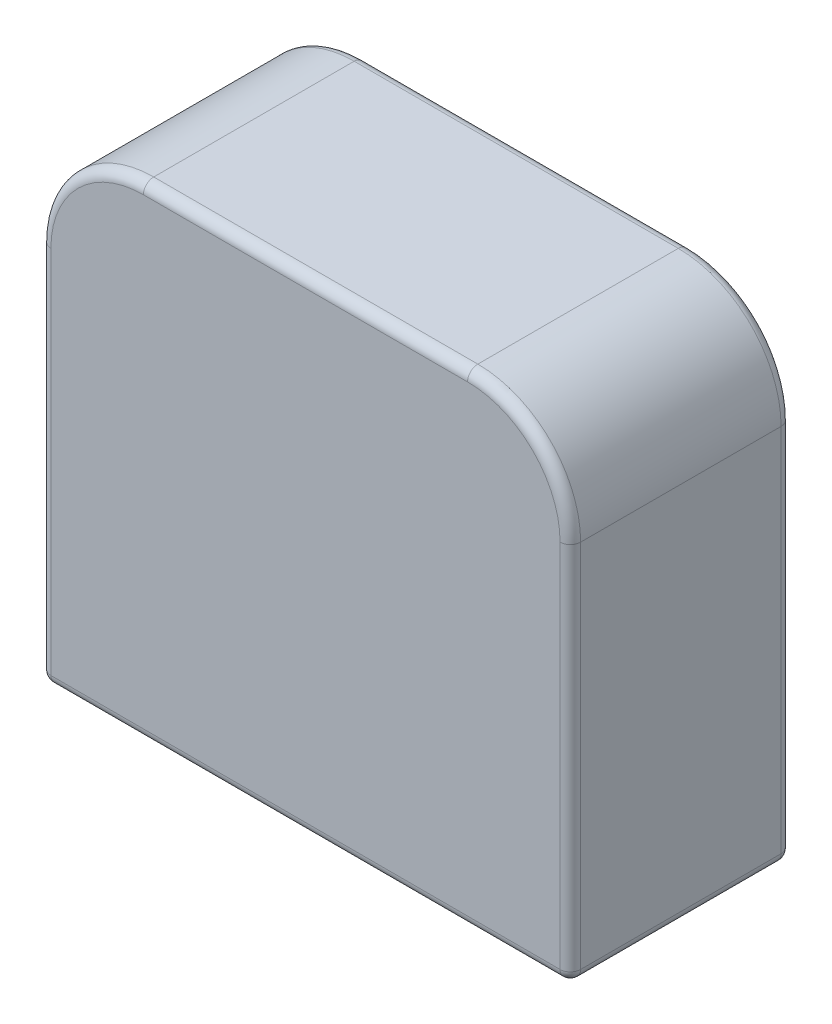
SolidWorks part; units mm, degrees
ref_plane "Alzado" through (0, 0, 0) normal (0, 0, 1) x (1, 0, 0)
ref_plane "Planta" through (0, 0, 0) normal (0, 1, 0) x (1, 0, 0)
ref_plane "Vista lateral" through (0, 0, 0) normal (1, 0, 0) x (0, 0, -1)
sketch "Croquis1" plane through (0, 0, 0) normal (0, 0, 1) x (1, 0, 0)
  line L1 (-25.765, 23.5) -> (25.765, 23.5)
  line L2 (-25.765, 23.5) -> (-25.765, -23.5)
  line L3 (-25.765, -23.5) -> (25.765, -23.5)
  line L4 (25.765, 23.5) -> (25.765, -23.5)
  line L5 (-25.765, 23.5) -> (25.765, -23.5) construction
  line L6 (-25.765, -23.5) -> (25.765, 23.5) construction
  point P0 (0, 0)
  dimension "D1" = 51.53
  dimension "D2" = 47
extrude "Saliente-Extruir1" add sketch "Croquis1" along normal blind 21.5
fillet "Redondeo4" radius 10 2 edges at (-25.765, 23.5, 10.75) (25.765, 23.5, 10.75)
fillet "Redondeo3" radius 1 14 edges at (-25.765, -23.5, 10.75) (0, -23.5, 0) (0, 23.5, 0) (-25.765, -5, 0) (25.765, -5, 0) (25.765, -23.5, 10.75) (0, -23.5, 21.5) (-25.765, -5, 21.5) (25.765, -5, 21.5) (0, 23.5, 21.5) (-22.8361, 20.5711, 0) (22.8361, 20.5711, 0) (-22.8361, 20.5711, 21.5) (22.8361, 20.5711, 21.5)
sketch "Croquis2" plane through (0, 0, 0) normal (0, 0, 1) x (1, 0, 0)
  line L0 (-15.765, 23.5) -> (15.765, 23.5) construction
  line L1 (25.765, 13.5) -> (25.765, -22.5) construction
  line L2 (24.765, -23.5) -> (-24.765, -23.5) construction
  line L3 (-25.765, -22.5) -> (-25.765, 13.5) construction
  line L4 (-15.765, 23.5) -> (15.765, 23.5)
  line L5 (25.765, 13.5) -> (25.765, -22.5)
  line L6 (24.765, -23.5) -> (-24.765, -23.5)
  line L7 (-25.765, -22.5) -> (-25.765, 13.5)
  arc A0 (25.765, 13.5) -> (15.765, 23.5) centre (15.765, 13.5) ccw construction
  arc A1 (24.765, -23.5) -> (25.765, -22.5) centre (24.765, -22.5) ccw construction
  arc A2 (-25.765, -22.5) -> (-24.765, -23.5) centre (-24.765, -22.5) ccw construction
  arc A3 (-15.765, 23.5) -> (-25.765, 13.5) centre (-15.765, 13.5) ccw construction
  arc A4 (25.765, 13.5) -> (15.765, 23.5) centre (15.765, 13.5) ccw
  arc A5 (24.765, -23.5) -> (25.765, -22.5) centre (24.765, -22.5) ccw
  arc A6 (-25.765, -22.5) -> (-24.765, -23.5) centre (-24.765, -22.5) ccw
  arc A7 (-15.765, 23.5) -> (-25.765, 13.5) centre (-15.765, 13.5) ccw
